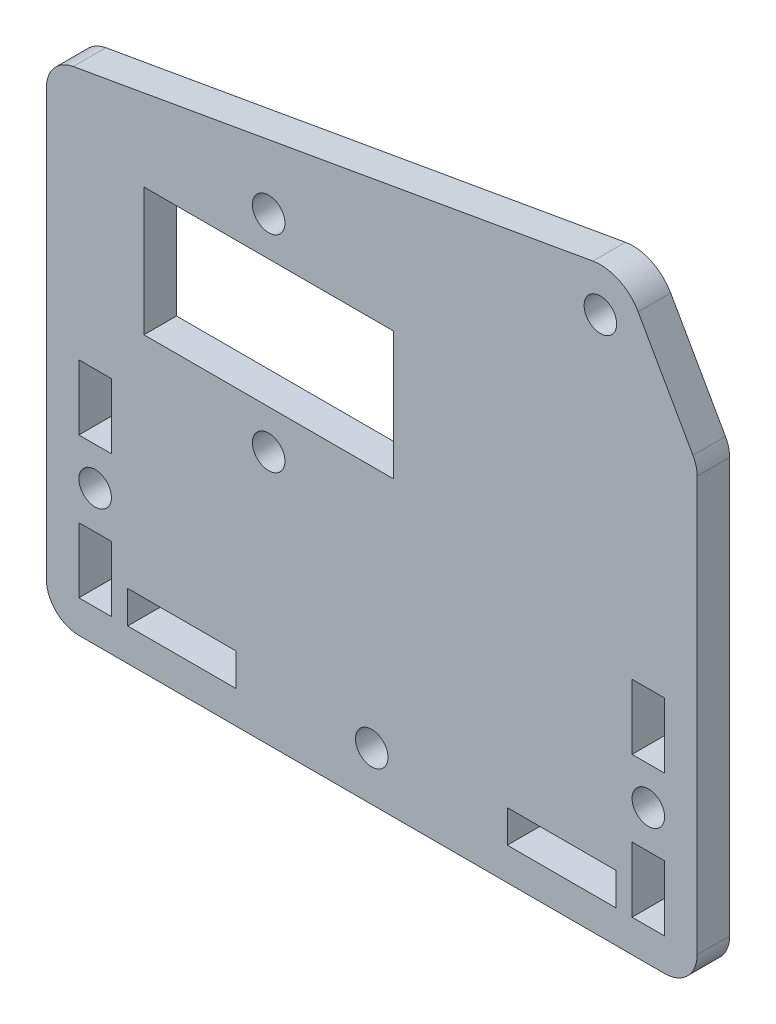
SolidWorks part; units mm, degrees
ref_plane "Plan de face" through (0, 0, 0) normal (0, 0, 1) x (1, 0, 0)
ref_plane "Plan de dessus" through (0, 0, 0) normal (0, 1, 0) x (1, 0, 0)
ref_plane "Plan de droite" through (0, 0, 0) normal (1, 0, 0) x (0, 0, -1)
sketch "Esquisse13" plane through (0, 0, 0) normal (0, 0, 1) x (1, 0, 0)
  line L0 (157.1252, -14.4258) -> (103.1252, -14.4258)
  line L1 (160.1252, -11.4258) -> (160.1252, 26.7842)
  line L2 (102.6059, 30.7358) -> (150.5124, 39.1554)
  line L3 (100.1252, -11.4258) -> (100.1252, 27.7811)
  line L4 (103.1252, -11.4258) -> (106.1252, -11.4258)
  line L5 (103.1252, -11.4258) -> (103.1252, -5.4258)
  line L6 (103.1252, -5.4258) -> (106.1252, -5.4258)
  line L7 (106.1252, -11.4258) -> (106.1252, -5.4258)
  line L8 (117.6252, -11.4258) -> (107.6252, -11.4258)
  line L9 (117.6252, -11.4258) -> (117.6252, -8.4258)
  line L10 (117.6252, -8.4258) -> (107.6252, -8.4258)
  line L11 (107.6252, -11.4258) -> (107.6252, -8.4258)
  line L12 (157.1252, -11.4258) -> (154.1252, -11.4258)
  line L13 (157.1252, -11.4258) -> (157.1252, -5.4258)
  line L14 (157.1252, -5.4258) -> (154.1252, -5.4258)
  line L15 (154.1252, -11.4258) -> (154.1252, -5.4258)
  line L16 (152.6252, -11.4258) -> (142.6252, -11.4258)
  line L17 (152.6252, -11.4258) -> (152.6252, -8.4258)
  line L18 (152.6252, -8.4258) -> (142.6252, -8.4258)
  line L19 (142.6252, -11.4258) -> (142.6252, -8.4258)
  line L20 (103.1252, 1.5742) -> (106.1252, 1.5742)
  line L21 (103.1252, 1.5742) -> (103.1252, 7.5742)
  line L22 (103.1252, 7.5742) -> (106.1252, 7.5742)
  line L23 (106.1252, 1.5742) -> (106.1252, 7.5742)
  line L24 (154.1252, 1.5742) -> (157.1252, 1.5742)
  line L25 (154.1252, 1.5742) -> (154.1252, 7.5742)
  line L26 (154.1252, 7.5742) -> (157.1252, 7.5742)
  line L27 (157.1252, 1.5742) -> (157.1252, 7.5742)
  line L28 (109.1252, 24.3742) -> (132.1252, 24.3742)
  line L29 (109.1252, 24.3742) -> (109.1252, 12.5742)
  line L30 (109.1252, 12.5742) -> (132.1252, 12.5742)
  line L31 (132.1252, 24.3742) -> (132.1252, 12.5742)
  line L32 (132.1252, 18.4742) -> (120.6252, 18.4742) construction
  line L33 (159.7362, 28.2617) -> (154.6861, 37.1858)
  arc A0 (103.1252, -14.4258) -> (100.1252, -11.4258) centre (103.1252, -11.4258) cw
  arc A1 (157.1252, -14.4258) -> (160.1252, -11.4258) centre (157.1252, -11.4258) ccw
  circle A2 centre (151.2048, 35.2158) radius 1.5
  arc A3 (102.6059, 30.7358) -> (100.1252, 27.7811) centre (103.1252, 27.7811) ccw
  circle A4 centre (130.1252, -9.9258) radius 1.5
  circle A5 centre (120.6252, 8.9742) radius 1.5
  circle A6 centre (120.6252, 27.9742) radius 1.5
  circle A7 centre (155.6252, -1.9258) radius 1.5
  circle A8 centre (104.6252, -1.9258) radius 1.5
  arc A9 (154.6861, 37.1858) -> (150.5124, 39.1554) centre (151.2048, 35.2158) ccw
  arc A10 (160.1252, 26.7842) -> (159.7362, 28.2617) centre (157.1252, 26.7842) ccw
  dimension "D1" = 3
  dimension "D14" = 3
  dimension "D15" = 3
  dimension "D17" = 3
  dimension "D26" = 3
  dimension "D27" = 3
  dimension "D33" = 3
  dimension "D36" = 8
  dimension "D37" = 3
  dimension "D32" = 19
  dimension "D34" = 9.5
  dimension "D2" = 3
  dimension "D3" = 3
  dimension "D4" = 6
  dimension "D5" = 6
  dimension "D6" = 10
  dimension "D7" = 3
  dimension "D8" = 3
  dimension "D9" = 10
  dimension "D10" = 45
  dimension "D11" = 1.5
  dimension "D12" = 1.5
  dimension "D13" = 1.5
  dimension "D16" = 1.5
  dimension "D18" = 3.5
  dimension "D19" = 3.5
  dimension "D20" = 6
  dimension "D21" = 6
  dimension "D22" = 3
  dimension "D23" = 3
  dimension "D24" = 3.5
  dimension "D25" = 3.5
  dimension "D28" = 11.8
  dimension "D29" = 23
  dimension "D30" = 9
  dimension "D31" = 11.5
  dimension "D35" = 12.5
  dimension "D38" = 27
extrude "Boss.-Extru.13" add sketch "Esquisse13" along normal blind 3 separate body
